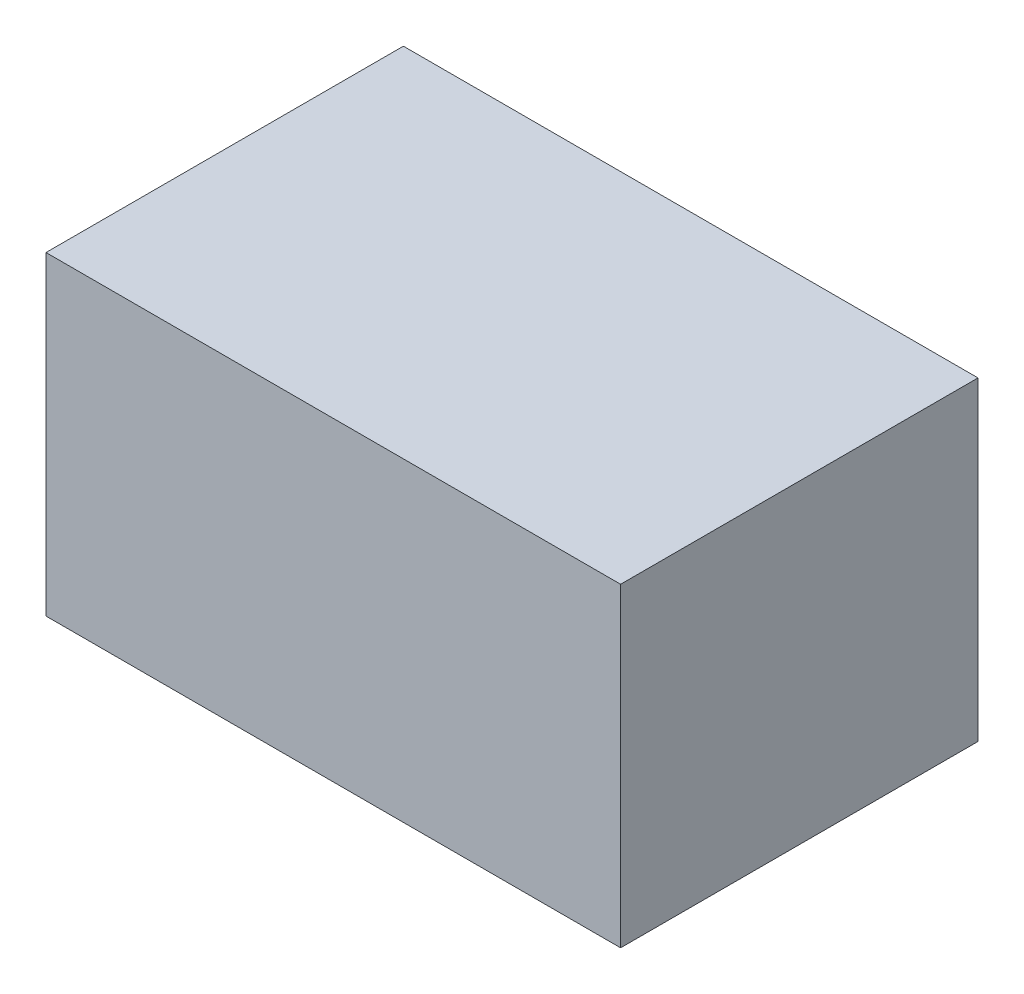
SolidWorks part; units mm, degrees
ref_plane "Front Plane" through (0, 0, 0) normal (0, 0, 1) x (1, 0, 0)
ref_plane "Top Plane" through (0, 0, 0) normal (0, 1, 0) x (1, 0, 0)
ref_plane "Right Plane" through (0, 0, 0) normal (1, 0, 0) x (0, 0, -1)
sketch "CurveSketch" plane through (0, 0, 0) normal (0, 0, 1) x (1, 0, 0)
  line L0 (-20.0525, -1.8635) -> (11.6665, -1.8635)
  line L1 (11.6665, -1.8635) -> (11.6665, 15.5175)
  line L2 (11.6665, 15.5175) -> (-20.0525, 15.5175)
  line L3 (-20.0525, 15.5175) -> (-20.0525, -1.8635)
extrude "CurveBoss" add sketch "CurveSketch" along normal mid plane 19.729
